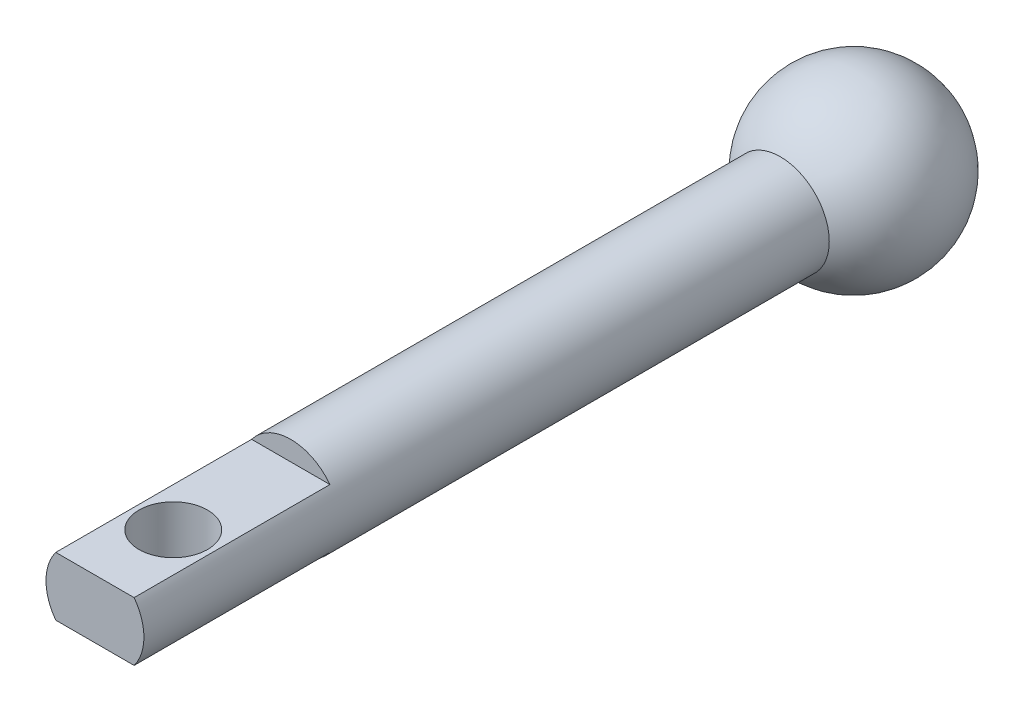
SolidWorks part; units mm, degrees
ref_plane "Front Plane" through (0, 0, 0) normal (0, 0, 1) x (1, 0, 0)
ref_plane "Top Plane" through (0, 0, 0) normal (0, 1, 0) x (1, 0, 0)
ref_plane "Right Plane" through (0, 0, 0) normal (1, 0, 0) x (0, 0, -1)
sketch "Sketch1" plane through (0, 0, 0) normal (0, 1, 0) x (1, 0, 0)
  line L0 (0, 43.2417) -> (0, 0)
  line L10 (0, 0) -> (2.5, 0)
  line L11 (2.5, 35) -> (2.5, 0)
  arc A0 (2.5, 35) -> (0, 43.2417) centre (0, 38.7417) ccw
  dimension "D1" = 4.5
  dimension "D2" = 35
  dimension "D3" = 2.5
revolve "Revolve1" add sketch "Sketch1" angle 360 about L0
sketch "Sketch2" plane through (0, 0, 0) normal (0, 0, 1) x (1, 0, 0)
  line L0 (-2, 1.5) -> (2, 1.5)
  line L5 (-2, -1.5) -> (2, -1.5)
  line L6 (5.0514, 0) -> (-4.2554, 0) construction
  line L7 (-5.635, 2.5) -> (4.7759, 2.5) construction
  circle A5 centre (0, 0) radius 2.5 construction
  circle A6 centre (0, 0) radius 2.5
  circle A7 centre (0, 0) radius 2.5 construction
  circle M12 centre (0, 0) radius 2.5
  dimension "D1" = 1
extrude "Cut-Extrude3" cut sketch "Sketch2" against normal blind 10 contours L0 M12 | L5 M12
sketch "Sketch4" plane through (0, 0, 0) normal (0, 1, 0) x (1, 0, 0)
  circle A0 centre (0, 4) radius 1.75
  dimension "D1" = 3.5
  dimension "D2" = 4
extrude "Cut-Extrude4" cut sketch "Sketch4" against normal through all both and the other way through all
